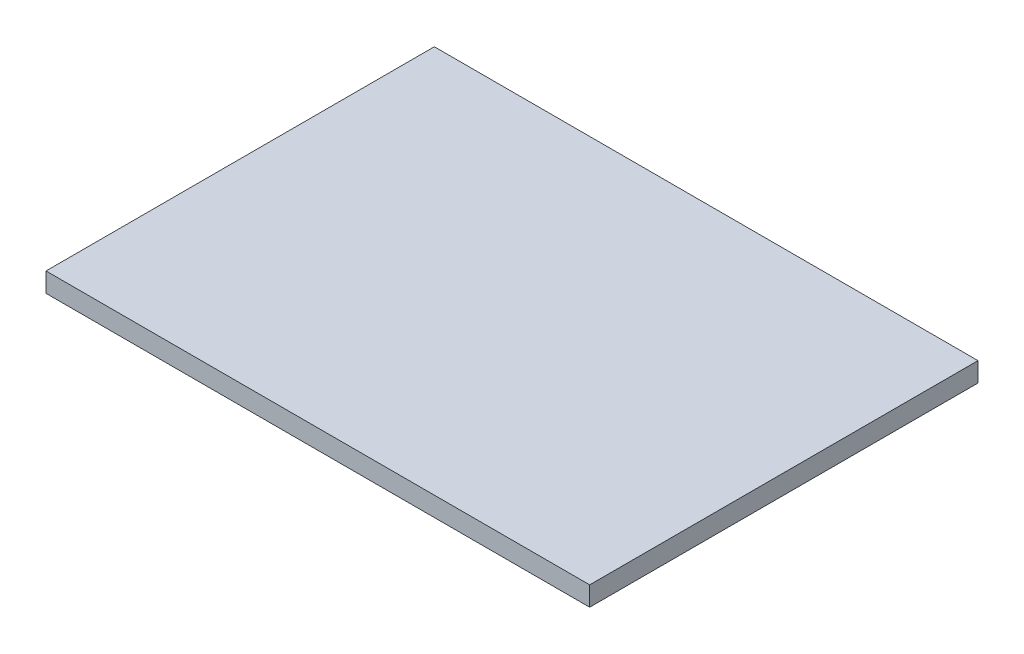
SolidWorks part; units mm, degrees
ref_plane "前视基准面" through (0, 0, 0) normal (0, 0, 1) x (1, 0, 0)
ref_plane "上视基准面" through (0, 0, 0) normal (0, 1, 0) x (1, 0, 0)
ref_plane "右视基准面" through (0, 0, 0) normal (1, 0, 0) x (0, 0, -1)
other "Configuration Table"
sketch "草图1" plane through (0, 0, 0) normal (0, 1, 0) x (1, 0, 0)
  line L1 (-70, 50) -> (70, 50)
  line L2 (-70, 50) -> (-70, -50)
  line L3 (-70, -50) -> (70, -50)
  line L4 (70, 50) -> (70, -50)
  line L5 (-70, 50) -> (70, -50) construction
  line L6 (-70, -50) -> (70, 50) construction
  point P0 (0, 0)
  dimension "D1" = 100
  dimension "D2" = 140
extrude "凸台-拉伸1" add sketch "草图1" along normal blind 5
